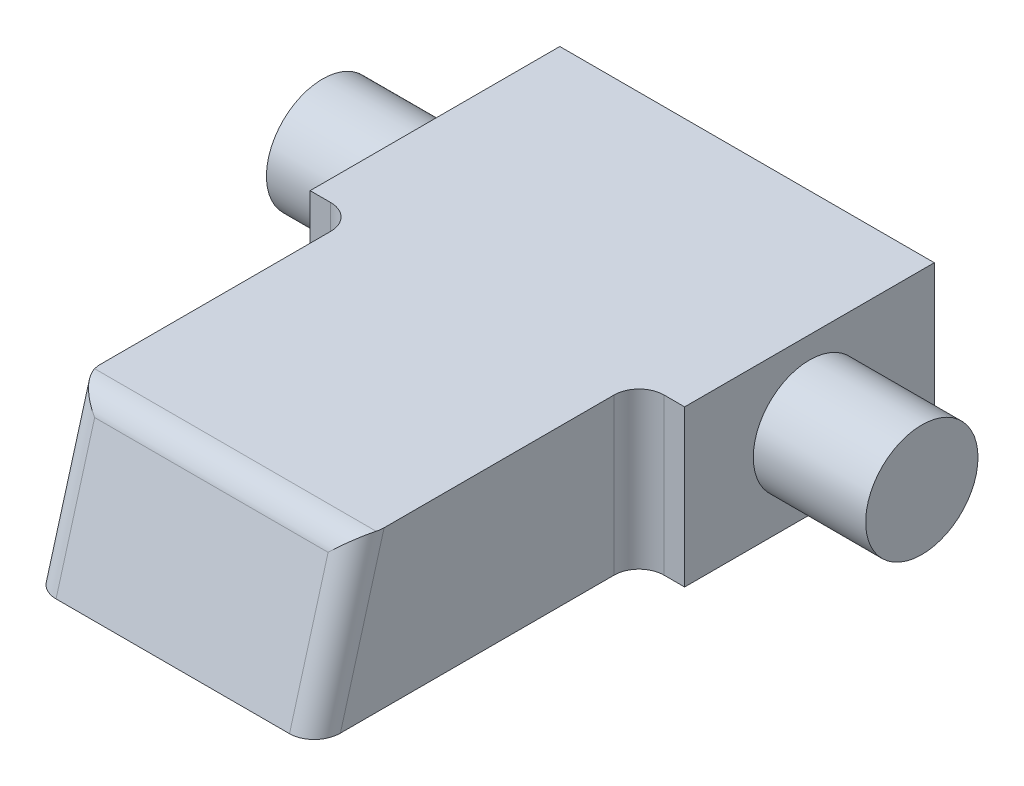
SolidWorks part; units mm, degrees
ref_plane "Front Plane" through (0, 0, 0) normal (0, 0, 1) x (1, 0, 0)
ref_plane "Top Plane" through (0, 0, 0) normal (0, 1, 0) x (1, 0, 0)
ref_plane "Right Plane" through (0, 0, 0) normal (1, 0, 0) x (0, 0, -1)
sketch "Sketch1" plane through (0, 0, 0) normal (0, 1, 0) x (1, 0, 0)
  line L0 (13.35, -10) -> (15, -10)
  line L1 (-15, 10) -> (15, 10)
  line L2 (-15, 10) -> (-15, -10)
  line L3 (-15, -10) -> (-13.35, -10)
  line L4 (15, 10) -> (15, -10)
  line L5 (-15, 10) -> (15, -10) construction
  line L6 (-15, -10) -> (15, 10) construction
  line L8 (-11.35, -12) -> (-11.35, -36)
  line L9 (-11.35, -36) -> (11.35, -36)
  line L10 (11.35, -12) -> (11.35, -36)
  line L11 (0, -36) -> (0, 0) construction
  arc A0 (13.35, -10) -> (11.35, -12) centre (13.35, -12) ccw
  arc A1 (-13.35, -10) -> (-11.35, -12) centre (-13.35, -12) cw
  point P0 (0, 0)
  point P14 (11.35, -10)
  dimension "D4" = 2
  dimension "D1" = 22.7
  dimension "D2" = 26
  dimension "D3" = 30
  dimension "D5" = 20
extrude "Boss-Extrude1" add sketch "Sketch1" along normal blind 12.5
sketch "Sketch2" plane through (0, 0, 0) normal (1, 0, 0) x (0, 0, -1)
  line L0 (-36, 0) -> (-32.5, 12.5)
  line L1 (-36, 12.5) -> (-12, 12.5) construction
  line L2 (-32.5, 12.5) -> (-36, 12.5)
  line L3 (-36, 12.5) -> (-36, 0)
  dimension "D1" = 3.5
extrude "Cut-Extrude1" cut sketch "Sketch2" against normal up to surface and the other way up to surface up to face at (-11.35, 6.25, 24) other way up to face at (11.35, 6.25, 24)
fillet "Fillet1" radius 2 3 edges at (-11.35, 6.25, 34.25) (11.35, 6.25, 34.25) (0, 12.5, 32.5)
sketch "Sketch3" plane through (0, 0, 0) normal (1, 0, 0) x (0, 0, -1)
  line L0 (0, 0) -> (0, 6.25) construction
  circle A0 centre (0, 6.25) radius 4.5
  dimension "D1" = 9
  dimension "D2" = 6.25
extrude "Boss-Extrude2" add sketch "Sketch3" along normal blind 24 and the other way blind 24
